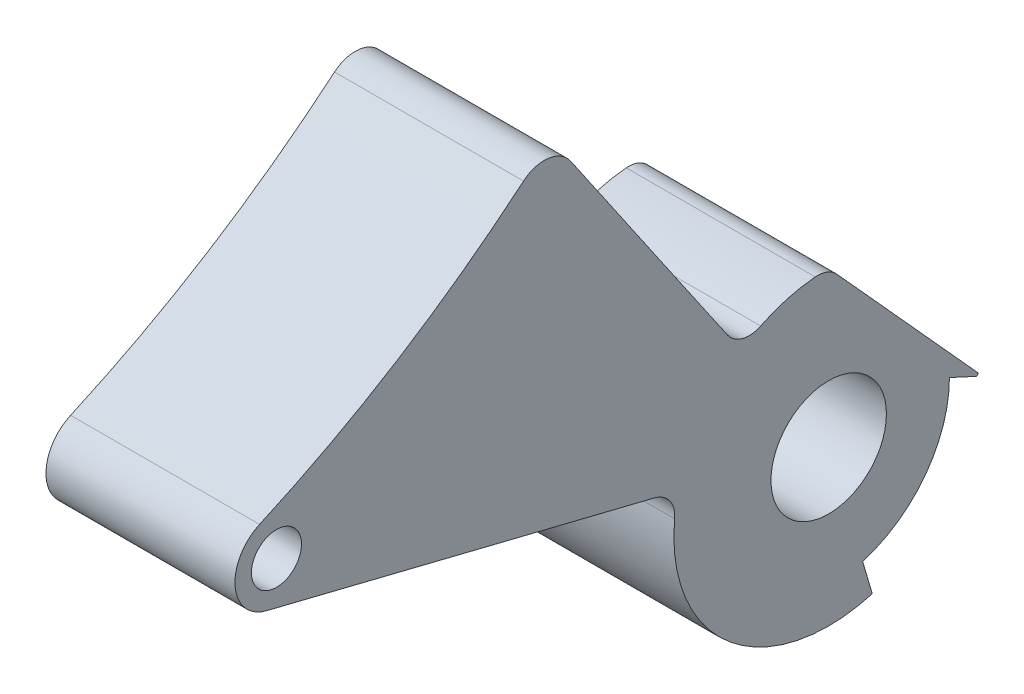
SolidWorks part; units mm, degrees
material "Plain Carbon Steel"
ref_plane "Front Plane" through (0, 0, 0) normal (0, 0, 1) x (1, 0, 0)
ref_plane "Top Plane" through (0, 0, 0) normal (0, 1, 0) x (1, 0, 0)
ref_plane "Right Plane" through (0, 0, 0) normal (1, 0, 0) x (0, 0, -1)
sketch "Sketch1" plane through (0, 0, 0) normal (1, 0, 0) x (0, 0, -1)
  line L0 (5.842, 0) -> (7.4557, -0.7464)
  line L1 (7.4557, -0.7464) -> (0, 7.493)
  line L2 (1.6426, -5.6063) -> (3.2852, -11.2126)
  line L3 (-4.2339, 6.1822) -> (-12.4837, 18.2284)
  line L5 (-27.2077, 6.7515) -> (-7.2724, 1.8046)
  circle A0 centre (0, 0) radius 2.794
  circle A1 centre (0, 0) radius 5.842
  circle A2 centre (0, 0) radius 7.493
  circle A3 centre (0, 0) radius 11.684
  arc A4 (-27.2077, 6.7515) -> (-27.5412, 10.5384) centre (-26.7236, 8.7023) cw
  arc A5 (-12.4837, 18.2284) -> (-14.7687, 18.5388) centre (-13.7667, 17.3497) ccw
  arc A6 (-27.5412, 10.5384) -> (-14.7687, 18.5388) centre (-49.4078, 59.6437) ccw
  circle A7 centre (-26.7236, 8.7023) radius 1.2125
  dimension "D1" = 5.588
  dimension "D2" = 11.684
  dimension "D3" = 14.986
  dimension "D4" = 23.368
  dimension "D7" = 1.555
  dimension "D5" = 5.842
  dimension "D6" = 1.778
extrude "Boss-Extrude1" add sketch "Sketch1" along normal blind 9.144
fillet "Fillet1" radius 0.0762 1 edges at (4.572, -0.7464, -7.4557)
fillet "Fillet2" radius 1.27 1 edges at (4.572, 6.1822, 4.2339)
fillet "Fillet3" radius 1.27 1 edges at (4.572, 7.493, 0)
fillet "Fillet4" radius 1.27 1 edges at (4.572, 1.8046, 7.2724)
